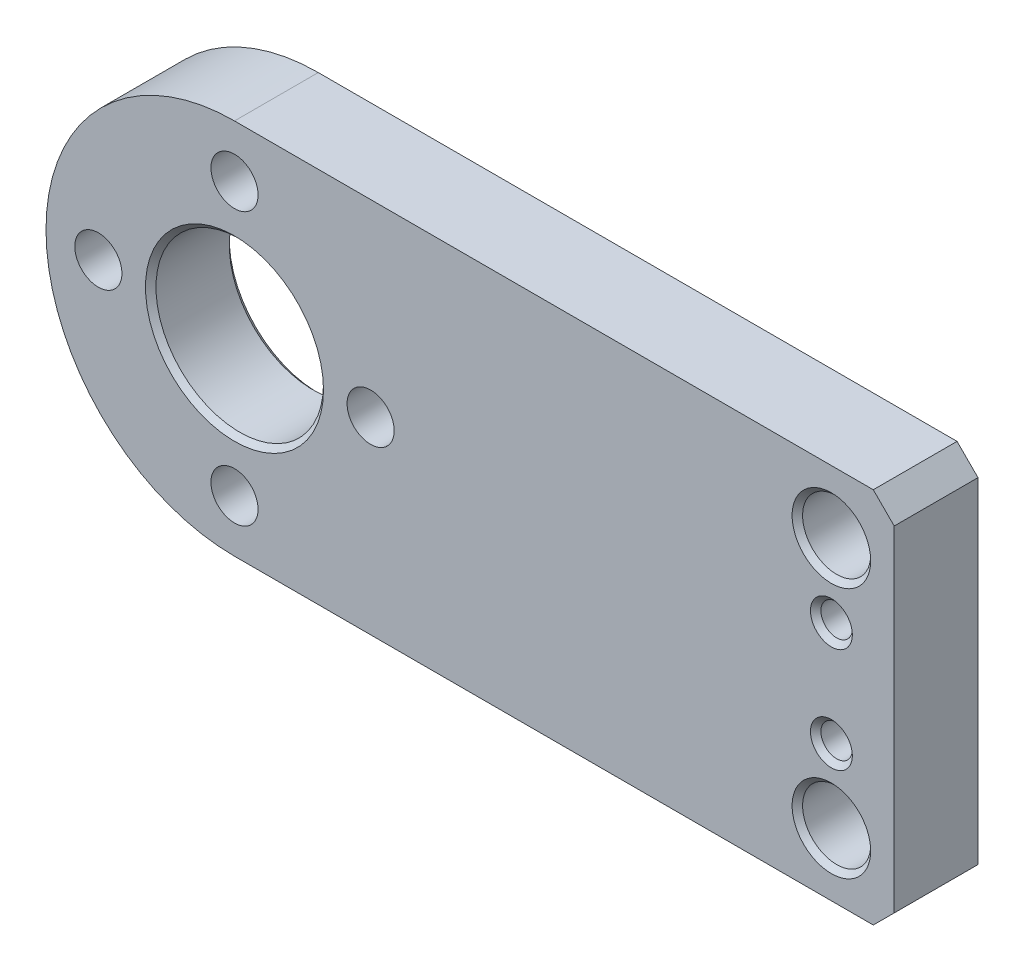
SolidWorks part; units mm, degrees
ref_plane "Front Plane" through (0, 0, 0) normal (0, 0, 1) x (1, 0, 0)
ref_plane "Top Plane" through (0, 0, 0) normal (0, 1, 0) x (1, 0, 0)
ref_plane "Right Plane" through (0, 0, 0) normal (1, 0, 0) x (0, 0, -1)
sketch "Sketch1" plane through (0, 0, 0) normal (0, 0, 1) x (1, 0, 0)
  line L0 (0, 0) -> (50000, 0) construction
  line L1 (-31.5, -18) -> (31.5, -18)
  line L2 (-31.5, -18) -> (-31.5, 18)
  line L3 (-31.5, 18) -> (31.5, 18)
  line L4 (31.5, -18) -> (31.5, 18)
  line L5 (-31.5, -18) -> (31.5, 18) construction
  line L6 (-31.5, 18) -> (31.5, -18) construction
  arc A0 (-31.5, 18) -> (-31.5, -18) centre (-31.5, 0) ccw
  circle A1 centre (-31.5, 0) radius 13 construction
  circle A2 centre (-31.5, 0) radius 8
  circle A3 centre (-31.5, 13) radius 2.25
  circle A4 centre (-18.5, 0) radius 2.25
  circle A5 centre (-31.5, -13) radius 2.25
  circle A6 centre (-44.5, 0) radius 2.25
  circle A7 centre (25.5, 12) radius 3.25
  circle A8 centre (25.5, 5) radius 1.5
  circle A9 centre (25.5, -5) radius 1.5
  circle A10 centre (25.5, -12) radius 3.25
  point P0 (0, 0)
  point P21 (-31.5, 0)
  dimension "D3" = 26
  dimension "D4" = 16
  dimension "D6" = 4.5
  dimension "D7" = 6.5
  dimension "D8" = 3
  dimension "D1" = 36
  dimension "D2" = 63
  dimension "D9" = 6
  dimension "D10" = 6
  dimension "D11" = 6
  dimension "D12" = 5
  dimension "D5" = 4
extrude "Boss-Extrude1" add sketch "Sketch1" along normal blind 8 contours A5 L2 A2 A3 A0 A6 | A5 L2 L1 L4 L3 A3 A2 A9 A8 A7 A4 A10
chamfer "Chamfer2" distance 2 angle 45 2 edges at (31.5, -18, 4) (31.5, 18, 4)
chamfer "Chamfer3" distance 0.5 angle 45 10 edges at (-23.5, 0, 0) (28.75, 12, 0) (27, 5, 0) (27, -5, 0) (28.75, -12, 0) (28.75, -12, 8) (27, -5, 8) (28.75, 12, 8) (27, 5, 8) (-23.5, 0, 8)
